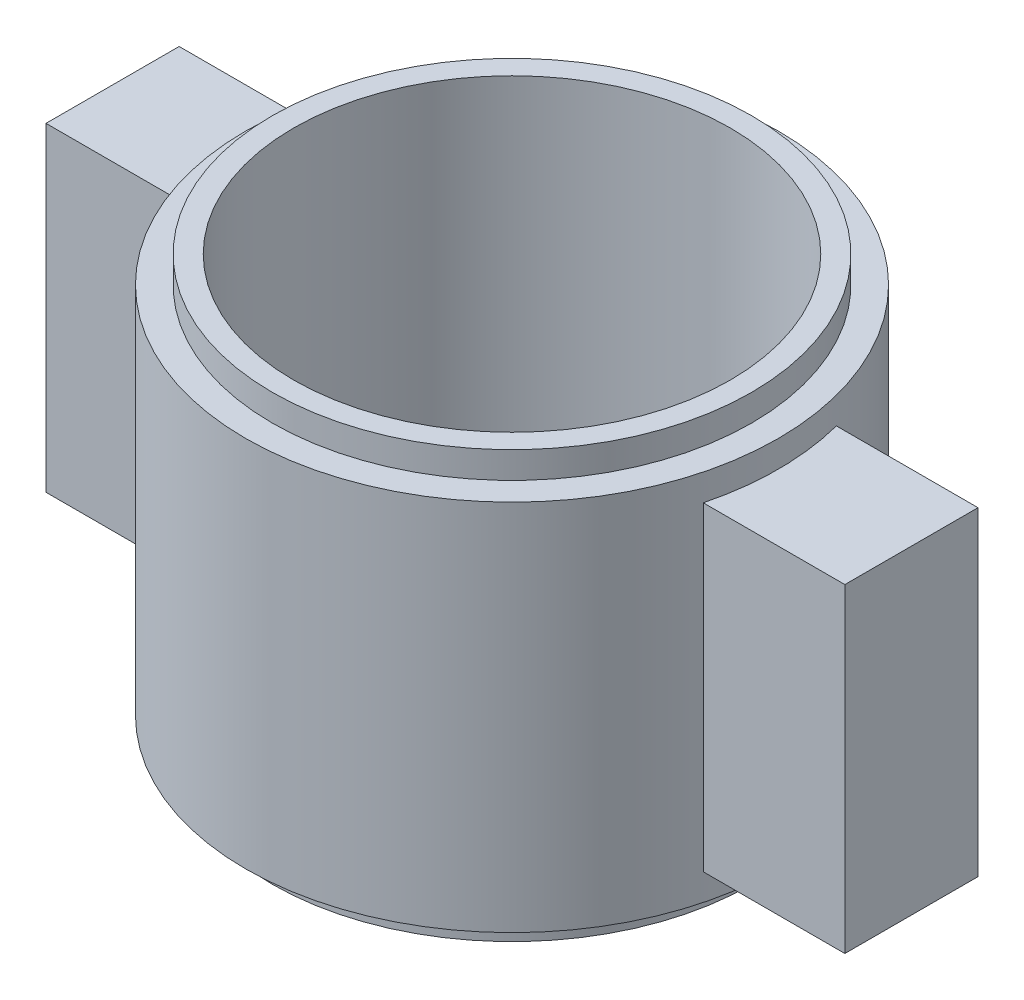
SolidWorks part; units mm, degrees
ref_plane "前视基准面" through (0, 0, 0) normal (0, 0, 1) x (1, 0, 0)
ref_plane "上视基准面" through (0, 0, 0) normal (0, 1, 0) x (1, 0, 0)
ref_plane "右视基准面" through (0, 0, 0) normal (1, 0, 0) x (0, 0, -1)
other "Configuration Table"
sketch "草图1" plane through (0, 0, 0) normal (0, 0, 1) x (1, 0, 0)
  line L0 (4.2, 0) -> (9, 0)
  line L1 (9, 0) -> (9, 1)
  line L2 (9, 1) -> (10, 1)
  line L3 (10, 1) -> (10, 15)
  line L4 (10, 15) -> (9, 15)
  line L5 (9, 15) -> (9, 16)
  line L6 (9, 16) -> (4.2, 16)
  line L7 (4.2, 16) -> (4.2, 0)
  line L8 (0, 0) -> (0, 16) construction
  dimension "x0" = 4.2
  dimension "x1" = 9
  dimension "x3" = 10
  dimension "x5" = 9
  dimension "y2" = 1
  dimension "y4" = 15
  dimension "y6" = 16
  dimension "y9" = 16
revolve "Round_nut" add sketch "草图1" angle 360 about L8
ref_plane "Tongue_plane" through (0, 0, -2.5) normal (0, 0, 1) x (1, 0, 0)
sketch "草图3" plane through (0, 0, -2.5) normal (0, 0, 1) x (1, 0, 0)
  line L0 (-8, 2) -> (-15, 2)
  line L1 (-15, 2) -> (-15, 14)
  line L2 (-15, 14) -> (-8, 14)
  line L3 (-8, 14) -> (-8, 2)
  dimension "x0" = 8
  dimension "x1" = 15
  dimension "y0" = 2
  dimension "y2" = 14
extrude "Continuous_tongue" add sketch "草图3" along normal blind 5
sketch "草图4" plane through (0, 0, -2.5) normal (0, 0, 1) x (1, 0, 0)
  line L0 (8, 2) -> (15, 2)
  line L1 (15, 2) -> (15, 14)
  line L2 (15, 14) -> (8, 14)
  line L3 (8, 14) -> (8, 2)
  dimension "x0" = 8
  dimension "x1" = 15
  dimension "y0" = 2
  dimension "y2" = 14
extrude "凸台-拉伸2" add sketch "草图4" along normal blind 5
sketch "草图5" plane through (0, 16, 0) normal (0, 1, 0) x (1, 0, 0)
  circle A0 centre (0, 0) radius 8.2
  dimension "diameter" = 16.4
extrude "D16_clearance" cut sketch "草图5" against normal through all
